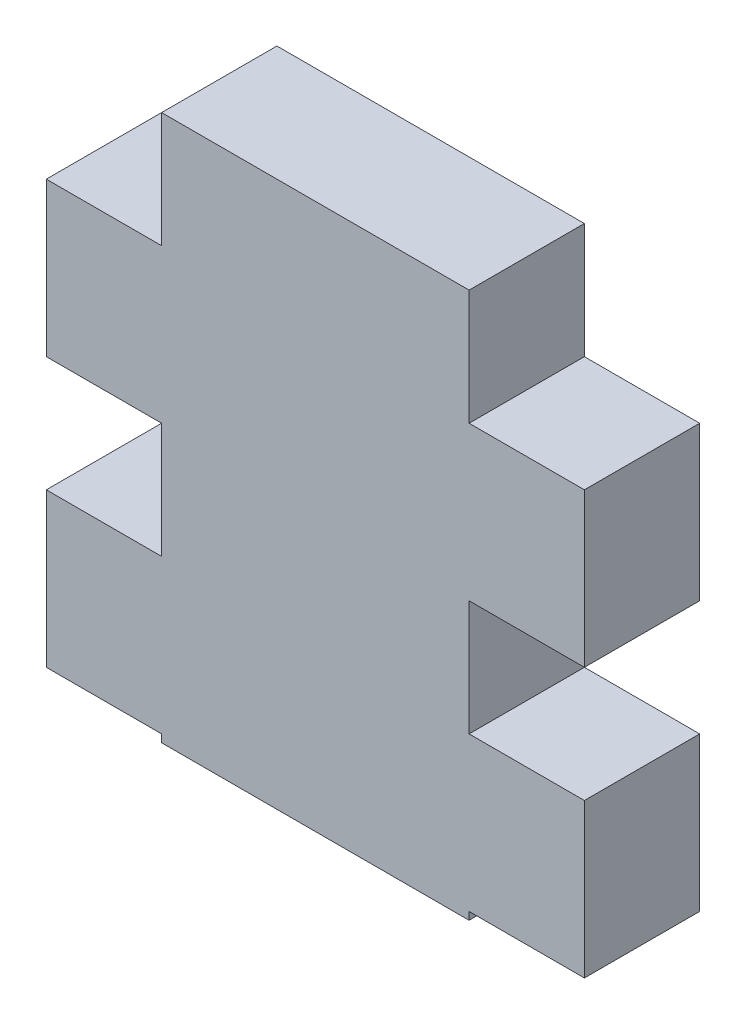
SolidWorks part; units mm, degrees
ref_plane "Plan de face" through (0, 0, 0) normal (0, 0, 1) x (1, 0, 0)
ref_plane "Plan de dessus" through (0, 0, 0) normal (0, 1, 0) x (1, 0, 0)
ref_plane "Plan de droite" through (0, 0, 0) normal (1, 0, 0) x (0, 0, -1)
sketch "Sketch1" plane through (0, 0, 0) normal (0, 0, 1) x (1, 0, 0)
  line L1 (-7, -7.1) -> (7, -7.1)
  line L2 (-7, -7.1) -> (-7, 7.1)
  line L3 (-7, 7.1) -> (7, 7.1)
  line L4 (7, -7.1) -> (7, 7.1)
  line L5 (-7, -7.1) -> (7, 7.1) construction
  line L6 (-7, 7.1) -> (7, -7.1) construction
  point P0 (0, 0)
  dimension "D1" = 14
  dimension "D2" = 14.2
extrude "Boss-Extrude1" add sketch "Sketch1" along normal blind 3
sketch "Sketch2" plane through (0, 0, 3) normal (0, 0, 1) x (1, 0, 0)
  line L0 (-7, 7.1) -> (-7, -7.1) construction
  line L1 (-7, 4.1) -> (-4, 4.1)
  line L2 (-7, 4.1) -> (-7, 7.1)
  line L3 (-7, 7.1) -> (-4, 7.1)
  line L4 (-4, 4.1) -> (-4, 7.1)
  line L5 (7, 7.1) -> (-7, 7.1) construction
  line L6 (-7, -7.1) -> (7, -7.1) construction
  line L7 (-7, 0.1) -> (-4, 0.1)
  line L8 (-7, 0.1) -> (-7, -2.9)
  line L9 (-7, -2.9) -> (-4, -2.9)
  line L10 (-4, 0.1) -> (-4, -2.9)
  line L12 (-7, -6.9) -> (-4, -6.9)
  line L13 (-7, -6.9) -> (-7, -7.1)
  line L14 (-7, -7.1) -> (-4, -7.1)
  line L15 (-4, -6.9) -> (-4, -7.1)
  dimension "D1" = 3
  dimension "D2" = 3
  dimension "D3" = 4
  dimension "D4" = 3
  dimension "D5" = 3
  dimension "D6" = 0.2
  dimension "D7" = 3
extrude "Cut-Extrude1" cut sketch "Sketch2" against normal blind 10
sketch "Sketch4" plane through (0, 0, 3) normal (0, 0, 1) x (1, 0, 0)
  line L0 (7, -7.1) -> (7, 7.1) construction
  line L1 (7, 4.1) -> (4, 4.1)
  line L2 (7, 4.1) -> (7, 7.1)
  line L3 (7, 7.1) -> (4, 7.1)
  line L4 (4, 4.1) -> (4, 7.1)
  line L5 (7, 7.1) -> (-4, 7.1) construction
  line L6 (-4, -7.1) -> (7, -7.1) construction
  line L7 (7, 0.1) -> (4, 0.1)
  line L8 (7, 0.1) -> (7, -2.9)
  line L9 (7, -2.9) -> (4, -2.9)
  line L10 (4, 0.1) -> (4, -2.9)
  line L11 (7, -6.9) -> (4, -6.9)
  line L12 (7, -6.9) -> (7, -7.1)
  line L13 (7, -7.1) -> (4, -7.1)
  line L14 (4, -6.9) -> (4, -7.1)
  dimension "D1" = 3
  dimension "D2" = 3
  dimension "D3" = 3
  dimension "D4" = 3
  dimension "D5" = 4
  dimension "D6" = 3
  dimension "D7" = 0.2
extrude "Cut-Extrude2" cut sketch "Sketch4" against normal blind 10
